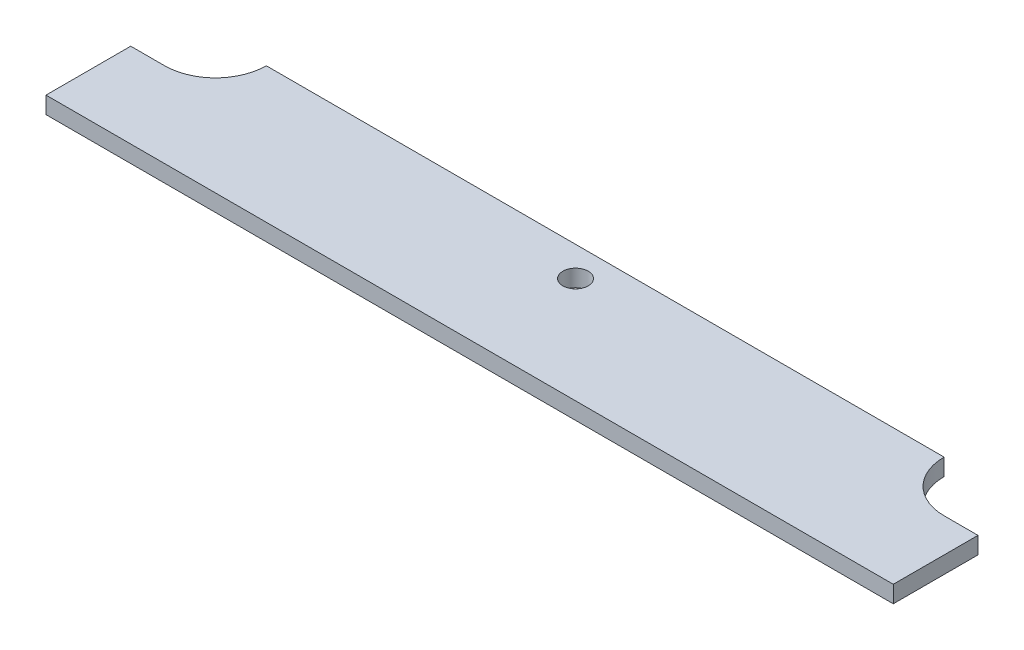
SolidWorks part; units mm, degrees
ref_plane "Front Plane" through (0, 0, 0) normal (0, 0, 1) x (1, 0, 0)
ref_plane "Top Plane" through (0, 0, 0) normal (0, 1, 0) x (1, 0, 0)
ref_plane "Right Plane" through (0, 0, 0) normal (1, 0, 0) x (0, 0, -1)
sketch "Sketch1" plane through (0, 0, 0) normal (0, 1, 0) x (1, 0, 0)
  line L1 (-317.5, 50.8) -> (317.5, 50.8)
  line L2 (-317.5, 50.8) -> (-317.5, -50.8)
  line L3 (-317.5, -50.8) -> (317.5, -50.8)
  line L4 (317.5, 50.8) -> (317.5, -50.8)
  line L5 (-317.5, 50.8) -> (317.5, -50.8) construction
  line L6 (-317.5, -50.8) -> (317.5, 50.8) construction
  point P0 (0, 0)
  dimension "D1" = 101.6
  dimension "D2" = 635
extrude "Boss-Extrude1" add sketch "Sketch1" along normal blind 12.7
sketch "Sketch2" plane through (0, 12.7, 0) normal (0, 1, 0) x (1, 0, 0)
  line L0 (317.5, 50.8) -> (-317.5, 50.8) construction
  line L1 (-317.5, 50.8) -> (-317.5, -50.8) construction
  line L2 (-292.1, 12.7) -> (-292.1, 50.8) construction
  line L3 (-292.1, 12.7) -> (-317.5, 12.7)
  line L4 (-317.5, 12.7) -> (-317.5, 50.8)
  line L5 (-317.5, 50.8) -> (-254, 50.8)
  arc A0 (-254, 50.8) -> (-292.1, 12.7) centre (-292.1, 50.8) cw
  dimension "D2" = 38.1
  dimension "D1" = 63.5
extrude "Cut-Extrude1" cut sketch "Sketch2" against normal through all
mirror "Mirror1" about plane through (0, 0, 0) normal (1, 0, 0) of "Cut-Extrude1"
sketch "Sketch3" plane through (0, 12.7, 0) normal (0, 1, 0) x (1, 0, 0)
  line L0 (0, 38.1) -> (0, 50.8) construction
  line L1 (254, 50.8) -> (-254, 50.8) construction
  circle A0 centre (0, 28.575) radius 9.525
  dimension "D1" = 19.05
  dimension "D2" = 12.7
extrude "Cut-Extrude2" cut sketch "Sketch3" against normal through all
